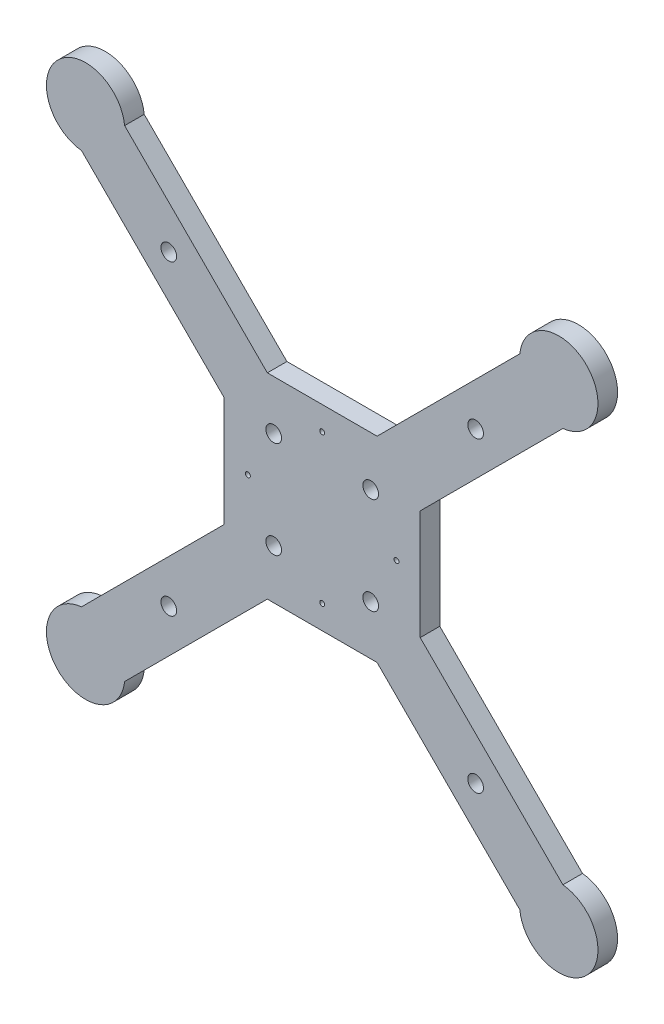
SolidWorks part; units mm, degrees
ref_plane "Plan de face" through (0, 0, 0) normal (0, 0, 1) x (1, 0, 0)
ref_plane "Plan de dessus" through (0, 0, 0) normal (0, 1, 0) x (1, 0, 0)
ref_plane "Plan de droite" through (0, 0, 0) normal (1, 0, 0) x (0, 0, -1)
sketch "Esquisse1" plane through (0, 0, 0) normal (0, 0, 1) x (1, 0, 0)
  line L0 (-50, 28) -> (-131.7107, 109.7107)
  line L1 (50, -50) -> (-50, -50)
  line L2 (50, -50) -> (50, 50)
  line L3 (50, 50) -> (-50, 50)
  line L4 (-50, -50) -> (-50, 50)
  line L5 (-131.7107, 109.7107) -> (-109.7107, 131.7107)
  line L6 (-109.7107, 131.7107) -> (-28, 50)
  line L7 (28, 50) -> (109.7107, 131.7107)
  line L8 (109.7107, 131.7107) -> (131.7107, 109.7107)
  line L9 (131.7107, 109.7107) -> (50, 28)
  line L10 (-50, -28) -> (-131.7107, -109.7107)
  line L11 (-131.7107, -109.7107) -> (-109.7107, -131.7107)
  line L12 (-109.7107, -131.7107) -> (-28, -50)
  line L13 (28, -50) -> (109.7107, -131.7107)
  line L14 (109.7107, -131.7107) -> (131.7107, -109.7107)
  line L15 (131.7107, -109.7107) -> (50, -28)
  line L16 (-50, 50) -> (50, -50) construction
  circle A0 centre (-120.7107, 120.7107) radius 20
  circle A1 centre (120.7107, 120.7107) radius 20
  circle A2 centre (120.7107, -120.7107) radius 20
  circle A3 centre (-120.7107, -120.7107) radius 20
  dimension "D16" = 40
  dimension "D17" = 40
  dimension "D18" = 40
  dimension "D19" = 40
  dimension "D1" = 100
  dimension "D3" = 22
  dimension "D4" = 22
  dimension "D2" = 22
  dimension "D5" = 22
  dimension "D6" = 22
  dimension "D7" = 22
  dimension "D8" = 22
  dimension "D9" = 22
  dimension "D10" = 45
  dimension "D11" = 45
  dimension "D12" = 100
  dimension "D13" = 100
  dimension "D14" = 100
  dimension "D15" = 100
extrude "Boss.-Extru.1" add sketch "Esquisse1" along normal blind 10 contours L6 A0 L0 L5 | L0 A0 L6 L5 | A0 L0 L4 L3 L6 | A1 L7 L3 L2 L9 | L9 A1 L7 L8 | L7 A1 L9 L8 | L4 L1 L2 L3 | L13 A2 L15 L14 | L15 A2 L13 L14 | A2 L15 L2 L1 L13 | L10 A3 L12 L11 | L12 A3 L10 L11 | A3 L12 L1 L4 L10
sketch "Esquisse3" plane through (0, 0, 0) normal (0, 0, -1) x (-1, 0, 0)
  line L0 (-134.8528, 134.8528) -> (134.8528, -134.8528) construction
  line L1 (-134.8528, -134.8528) -> (134.8528, 134.8528) construction
  line L2 (0, 0) -> (-24.7487, 24.7487) construction
  line L3 (0, 0) -> (24.7487, 24.7487) construction
  line L4 (-50, 0) -> (50, 0) construction
  line L5 (-50, -28) -> (-50, 28) construction
  line L6 (50, -28) -> (50, 28) construction
  line L7 (0, 0) -> (-37.92, 0) construction
  line L8 (0, 0) -> (0, 37.92) construction
  arc A0 (-100.8225, 122.8225) -> (-122.8225, 100.8225) centre (-120.7107, 120.7107) ccw construction
  arc A1 (100.8225, -122.8225) -> (122.8225, -100.8225) centre (120.7107, -120.7107) ccw construction
  arc A2 (-122.8225, -100.8225) -> (-100.8225, -122.8225) centre (-120.7107, -120.7107) ccw construction
  arc A3 (122.8225, 100.8225) -> (100.8225, 122.8225) centre (120.7107, 120.7107) ccw construction
  circle A4 centre (-78.2843, 78.2843) radius 4
  circle A5 centre (-24.7487, 24.7487) radius 4
  circle A6 centre (78.2843, 78.2843) radius 4
  circle A7 centre (24.7487, 24.7487) radius 4
  circle A8 centre (78.2843, -78.2843) radius 4
  circle A9 centre (24.7487, -24.7487) radius 4
  circle A10 centre (-78.2843, -78.2843) radius 4
  circle A11 centre (-24.7487, -24.7487) radius 4
  circle A12 centre (-37.92, 0) radius 1.25
  circle A13 centre (0, 37.92) radius 1.25
  circle A14 centre (37.92, 0) radius 1.25
  circle A15 centre (0, -37.92) radius 1.25
  point P44 (39.3207, 10.4035)
  point P45 (0, 0)
  dimension "D1" = 8
  dimension "D2" = 8
  dimension "D7" = 2.5
  dimension "D3" = 80
  dimension "D4" = 35
  dimension "D6" = 90
  dimension "D10" = 90
  dimension "D11" = 37.92
  dimension "D5" = 4
  dimension "D9" = 4
extrude "Enlèv. mat.-Extru.2" cut sketch "Esquisse3" against normal through all
equation "\"L\"= 100"
equation "\"e\"= 22"
equation "\"D15@Esquisse1\"=\"L\""
equation "\"D14@Esquisse1\"=\"L\""
equation "\"D13@Esquisse1\"=\"L\""
equation "\"D12@Esquisse1\"=\"L\""
equation "\"D8@Esquisse1\"=\"e\""
equation "\"D9@Esquisse1\"=\"e\""
equation "\"D3@Esquisse1\"=\"e\""
equation "\"D4@Esquisse1\"=\"e\""
equation "\"D2@Esquisse1\"=\"e\""
equation "\"D5@Esquisse1\"=\"e\""
equation "\"D6@Esquisse1\"=\"e\""
equation "\"D7@Esquisse1\"=\"e\""
equation "\"d\"= 40"
equation "\"D17@Esquisse1\"=\"d\""
equation "\"D16@Esquisse1\"=\"d\""
equation "\"D19@Esquisse1\"=\"d\""
equation "\"D18@Esquisse1\"=\"d\""
